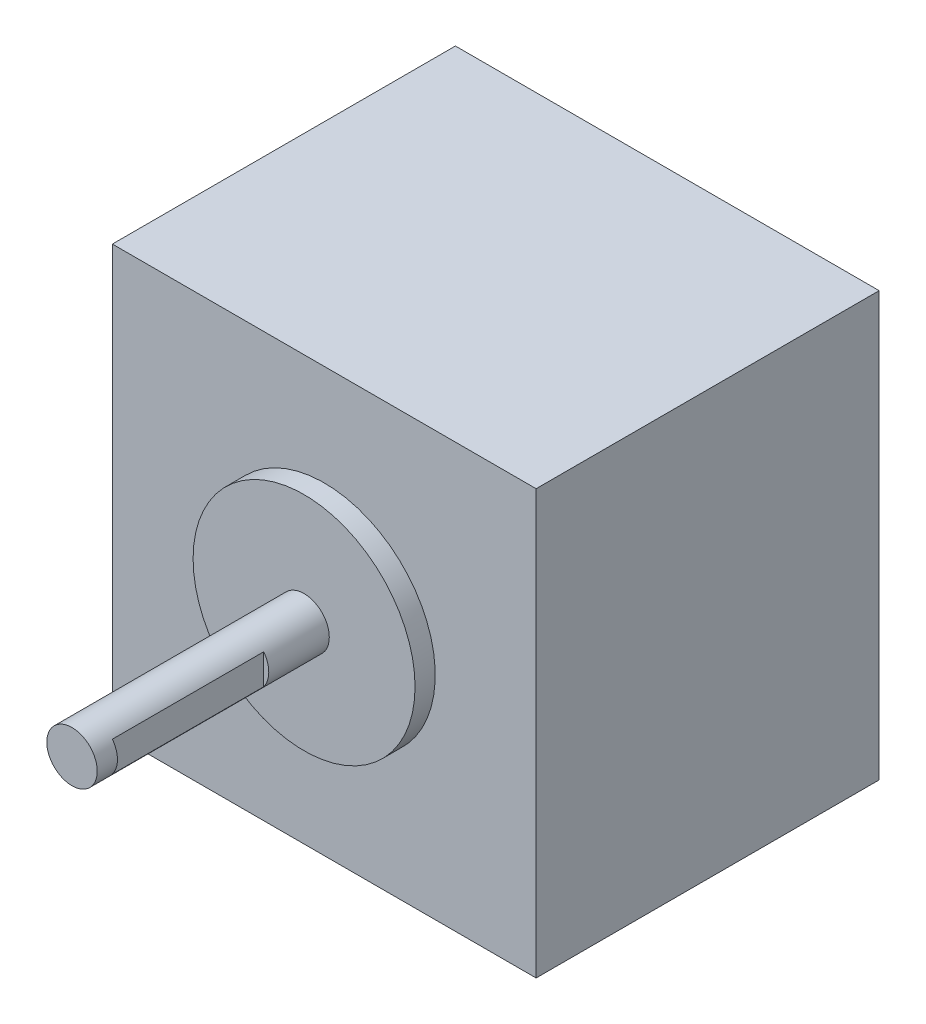
SolidWorks part; units mm, degrees
ref_plane "Front Plane" through (0, 0, 0) normal (0, 0, 1) x (1, 0, 0)
ref_plane "Top Plane" through (0, 0, 0) normal (0, 1, 0) x (1, 0, 0)
ref_plane "Right Plane" through (0, 0, 0) normal (1, 0, 0) x (0, 0, -1)
sketch "Sketch1" plane through (0, 0, 0) normal (0, 0, 1) x (1, 0, 0)
  line L1 (-21, -21) -> (21, -21)
  line L2 (-21, -21) -> (-21, 21)
  line L3 (-21, 21) -> (21, 21)
  line L4 (21, -21) -> (21, 21)
  line L5 (-21, -21) -> (21, 21) construction
  line L6 (-21, 21) -> (21, -21) construction
  point P0 (0, 0)
  dimension "D1" = 21
extrude "Boss-Extrude1" add sketch "Sketch1" against normal blind 34
sketch "Sketch2" plane through (0, 0, 0) normal (0, 0, 1) x (1, 0, 0)
  circle A0 centre (0, 0) radius 2.5
  dimension "D1" = 5
extrude "Boss-Extrude2" add sketch "Sketch2" along normal blind 25
sketch "Sketch3" plane through (0, 0, 0) normal (0, 0, 1) x (1, 0, 0)
  circle A0 centre (0, 0) radius 11
extrude "Boss-Extrude3" add sketch "Sketch3" along normal blind 2
ref_plane "Mat_cat_truc" through (0, 0, 23) normal (0, 0, 1) x (1, 0, 0)
sketch "Sketch4" plane through (0, 0, 23) normal (0, 0, 1) x (1, 0, 0)
  line L1 (2, -3) -> (3, -3)
  line L2 (2, -3) -> (2, 3)
  line L3 (2, 3) -> (3, 3)
  line L4 (3, -3) -> (3, 3)
extrude "Cut-Extrude1" cut sketch "Sketch4" against normal blind 15
